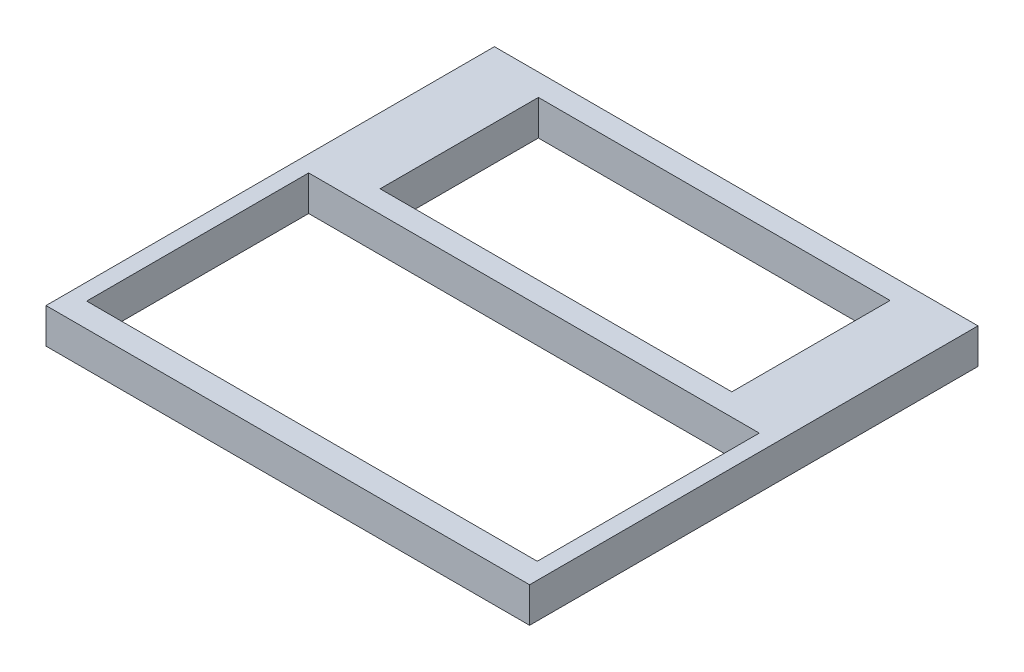
SolidWorks part; units mm, degrees
ref_plane "Front Plane" through (0, 0, 0) normal (0, 0, 1) x (1, 0, 0)
ref_plane "Top Plane" through (0, 0, 0) normal (0, 1, 0) x (1, 0, 0)
ref_plane "Right Plane" through (0, 0, 0) normal (1, 0, 0) x (0, 0, -1)
sketch "Sketch1" plane through (0, 0, 0) normal (0, 1, 0) x (1, 0, 0)
  line L1 (-55, -51) -> (55, -51)
  line L2 (-55, -51) -> (-55, 51)
  line L3 (-55, 51) -> (55, 51)
  line L4 (55, -51) -> (55, 51)
  line L5 (-55, -51) -> (55, 51) construction
  line L6 (-55, 51) -> (55, -51) construction
  line L7 (-40, 46) -> (40, 46)
  line L8 (-40, 46) -> (-40, 10)
  line L9 (-40, 10) -> (40, 10)
  line L10 (40, 46) -> (40, 10)
  point P0 (0, 0)
  dimension "D1" = 110
  dimension "D2" = 102
  dimension "D3" = 36
  dimension "D4" = 80
  dimension "D5" = 15
  dimension "D6" = 5
extrude "Boss-Extrude1" add sketch "Sketch1" along normal blind 8
sketch "Sketch2" plane through (0, 8, 0) normal (0, 1, 0) x (1, 0, 0)
  line L0 (-55, 51) -> (-55, -51) construction
  line L1 (-51.25, 5) -> (51.25, 5)
  line L2 (-51.25, 5) -> (-51.25, -45.5)
  line L3 (-51.25, -45.5) -> (51.25, -45.5)
  line L4 (51.25, 5) -> (51.25, -45.5)
  line L5 (-40, 10) -> (40, 10) construction
  dimension "D1" = 50.5
  dimension "D2" = 102.5
  dimension "D3" = 3.75
  dimension "D4" = 5
extrude "Cut-Extrude1" cut sketch "Sketch2" against normal blind 8
